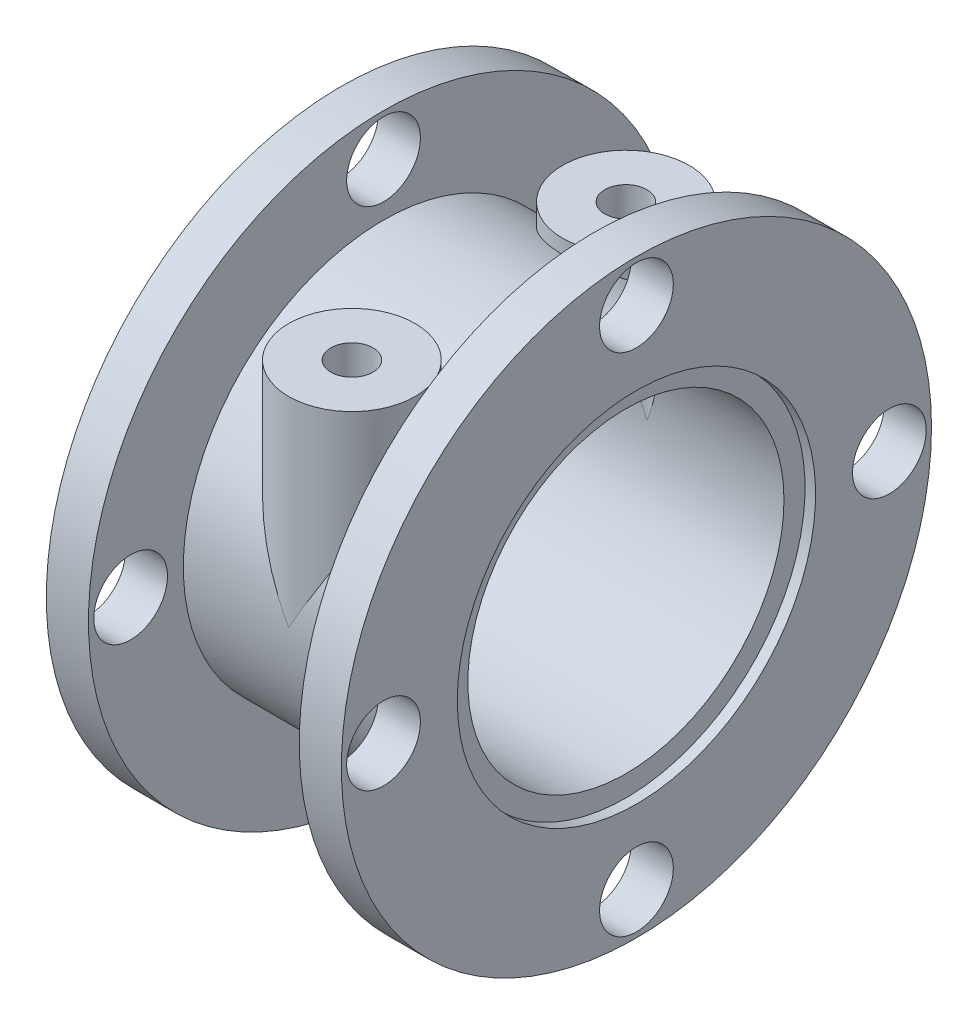
SolidWorks part; units mm, degrees
ref_plane "Front Plane" through (0, 0, 0) normal (0, 0, 1) x (1, 0, 0)
ref_plane "Top Plane" through (0, 0, 0) normal (0, 1, 0) x (1, 0, 0)
ref_plane "Right Plane" through (0, 0, 0) normal (1, 0, 0) x (0, 0, -1)
sketch "Sketch2" plane through (0, 0, 0) normal (1, 0, 0) x (0, 0, -1)
  circle A0 centre (0, 0) radius 14
  circle A1 centre (0, 12) radius 1.75
  circle A2 centre (12, 0) radius 1.75
  circle A3 centre (0, -12) radius 1.75
  circle A4 centre (-12, 0) radius 1.75
  circle A5 centre (0, 0) radius 7.5
  circle A6 centre (0, 0) radius 8.5 construction
  point P14 (0, 0)
  dimension "D1" = 28
  dimension "D3" = 3.5
  dimension "D5" = 15
  dimension "D6" = 17
  dimension "D4" = 12
  dimension "D2" = 4
extrude "Flange" add sketch "Sketch2" against normal blind 2
sketch "Sketch3" plane through (-2, 0, 0) normal (-1, 0, 0) x (0, 0, 1)
  circle A0 centre (0, 0) radius 8.5
  dimension "D1" = 17
extrude "O-Ring Seat" cut sketch "Sketch3" against normal blind 0.5
sketch "Sketch4" plane through (0, 0, 0) normal (1, 0, 0) x (0, 0, -1)
  circle A0 centre (0, 0) radius 7.5
  circle A1 centre (0, 0) radius 9.5
  dimension "D1" = 2
extrude "Boss-Extrude1" add sketch "Sketch4" along normal blind 10
ref_plane "MidPlane Reference" through (5, 0, 0) normal (1, 0, 0) x (0, 0, -1)
mirror "Mirror1" about plane through (5, 0, 0) normal (1, 0, 0) of "O-Ring Seat", "Flange"
sketch "Sketch5" plane through (0, 0, 0) normal (0, 1, 0) x (1, 0, 0)
  line L0 (5, -15.4) -> (5, 15.4) construction
  circle A0 centre (5, 6.5) radius 1
  point P2 (0, 0)
  dimension "D1" = 2
  dimension "D2" = 6.5
extrude "Outlet" cut sketch "Sketch5" along normal through all
ref_plane "Plane2" through (0, 9.5, 0) normal (0, 1, 0) x (1, 0, 0)
sketch "Sketch6" plane through (0, 9.5, 0) normal (0, 1, 0) x (1, 0, 0)
  circle A2 centre (5, 6.5) radius 1
  circle A3 centre (5, 6.5) radius 3
  dimension "D1" = 2
extrude "Boss-Extrude2" add sketch "Sketch6" against normal up to next
mirror "Inlet" about plane through (0, 0, 0) normal (0, 0, 1) of "Boss-Extrude2", "Outlet"
